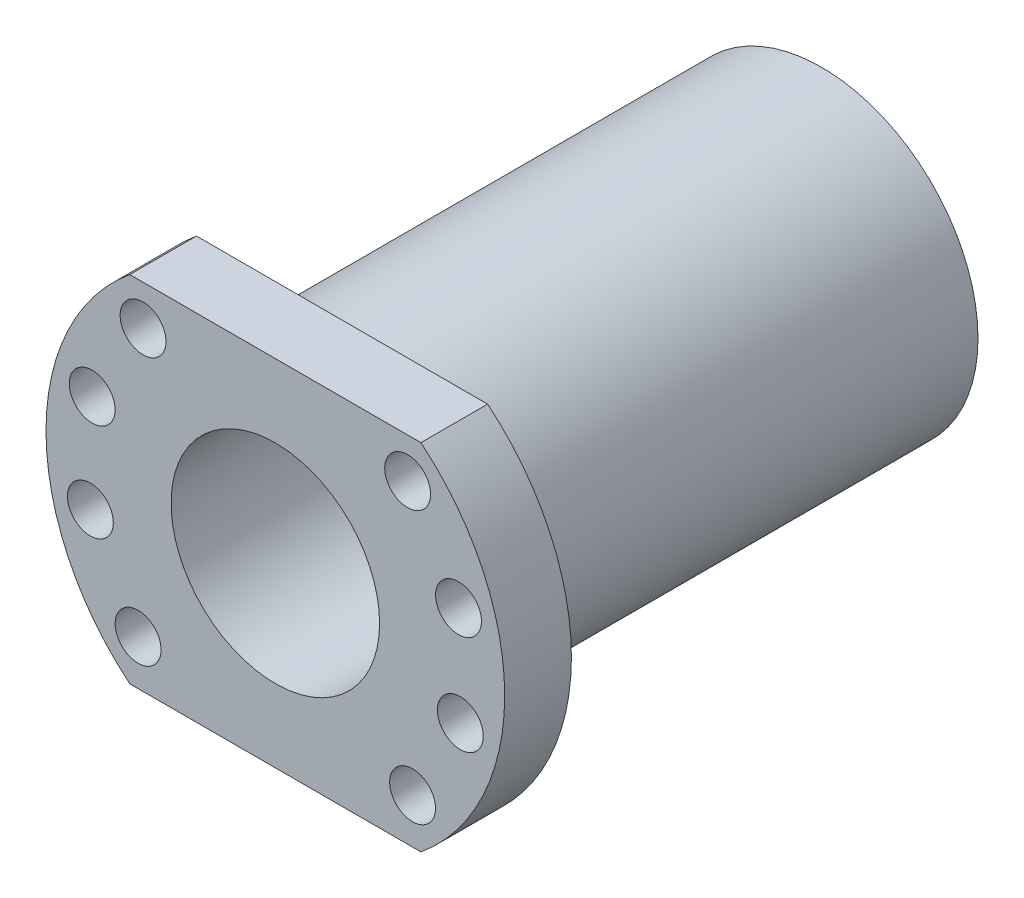
SolidWorks part; units mm, degrees
ref_plane "前视基准面" through (0, 0, 0) normal (0, 0, 1) x (1, 0, 0)
ref_plane "上视基准面" through (0, 0, 0) normal (0, 1, 0) x (1, 0, 0)
ref_plane "右视基准面" through (0, 0, 0) normal (1, 0, 0) x (0, 0, -1)
other "Configuration Table"
sketch "草图1" plane through (0, 0, 0) normal (0, 0, 1) x (1, 0, 0)
  line L0 (-34.9106, 42.5) -> (34.9106, 42.5)
  line L1 (-66.2195, 0) -> (76.7049, 0) construction
  line L2 (-34.9106, -42.5) -> (34.9106, -42.5)
  line L3 (0, -53.0724) -> (0, 0) construction
  arc A0 (-34.9106, 42.5) -> (-34.9106, -42.5) centre (0, 0) ccw
  arc A1 (34.9106, -42.5) -> (34.9106, 42.5) centre (0, 0) ccw
  circle A2 centre (0, 0) radius 25
  dimension "D1" = 110
  dimension "D3" = 50
  dimension "D2" = 42.5
extrude "凸台-拉伸1" add sketch "草图1" along normal blind 16
sketch "草图2" plane through (0, 0, 16) normal (0, 0, 1) x (1, 0, 0)
  line L0 (0, 0) -> (0, 54.7694) construction
  circle A0 centre (-31.7239, 32.9081) radius 5.5
  circle A1 centre (-43.9278, 12.6373) radius 5.5
  circle A2 centre (-44.3612, -11.0197) radius 5.5
  circle A3 centre (-32.9081, -31.7239) radius 5.5
  circle A4 centre (32.9081, -31.7239) radius 5.5
  circle A5 centre (44.3612, -11.0197) radius 5.5
  circle A6 centre (43.9278, 12.6373) radius 5.5
  circle A7 centre (31.7239, 32.9081) radius 5.5
  point P12 (0, 0)
  dimension "D1" = 11
  dimension "D2" = 45.7094
  dimension "D3" = 4
extrude "切除-拉伸1" cut sketch "草图2" against normal through all
sketch "草图3" plane through (0, 0, 0) normal (0, 0, -1) x (-1, 0, 0)
  circle A0 centre (0, 0) radius 37.5
  dimension "D1" = 75
extrude "凸台-拉伸2" add sketch "草图3" along normal blind 115
sketch "草图4" plane through (0, 0, 0) normal (0, 0, 1) x (1, 0, 0)
  circle A0 centre (0, 0) radius 25
extrude "切除-拉伸2" cut sketch "草图4" against normal through all
